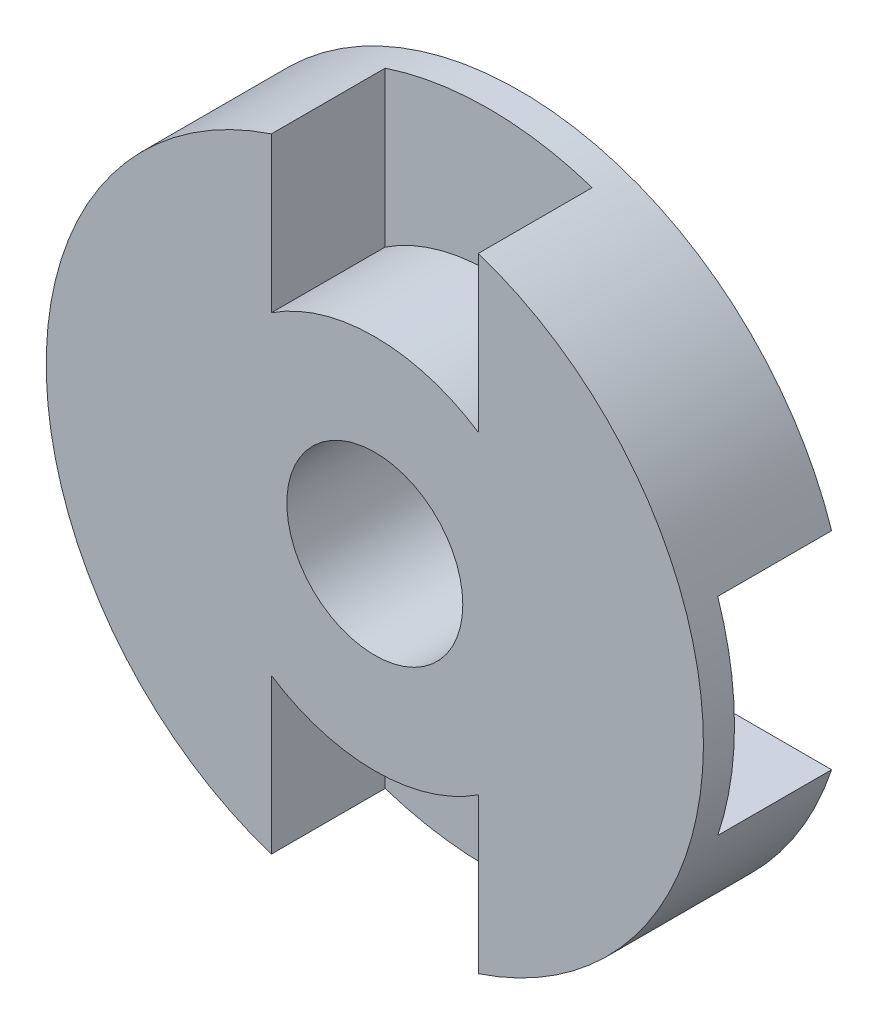
SolidWorks part; units mm, degrees
ref_plane "Front" through (0, 0, 0) normal (0, 0, 1) x (1, 0, 0)
ref_plane "Top" through (0, 0, 0) normal (0, 1, 0) x (1, 0, 0)
ref_plane "Right" through (0, 0, 0) normal (1, 0, 0) x (0, 0, -1)
sketch "Sketch1" plane through (0, 0, 0) normal (0, 0, 1) x (1, 0, 0)
  circle A0 centre (0, 0) radius 6.35
  point P3 (0, 6.35)
extrude "Boss-Extrude1" add sketch "Sketch1" against normal mid plane 2.8
sketch "Sketch2" plane through (0, 0, 1.4) normal (0, 0, 1) x (1, 0, 0)
  line L0 (-2, 6.35) -> (2, -6.35) construction
  line L1 (-2, 6.35) -> (2, 6.35)
  line L2 (-2, 6.35) -> (-2, -6.35)
  line L3 (-2, -6.35) -> (2, -6.35)
  line L4 (2, 6.35) -> (2, -6.35)
  circle A0 centre (0, 0) radius 6.35 construction
extrude "Cut-Extrude1" cut sketch "Sketch2" against normal blind 2.2
sketch "Sketch3" plane through (0, 0, -1.4) normal (0, 0, -1) x (-1, 0, 0)
  line L1 (-6.35, 2) -> (6.35, 2)
  line L2 (-6.35, 2) -> (-6.35, -2)
  line L3 (-6.35, -2) -> (6.35, -2)
  line L4 (6.35, 2) -> (6.35, -2)
  line L14 (2, 6.35) -> (-2, 6.35) construction
  line L15 (6.35, 2) -> (-6.35, -2) construction
  circle A0 centre (0, 0) radius 6.35 construction
extrude "Cut-Extrude2" cut sketch "Sketch3" against normal blind 2.2
sketch "Sketch4" [suppressed] plane through (0, 0, 8.5344) normal (0, 0, 1) x (1, 0, 0)
  line L0 (-5.0483, 0) -> (-8.6297, 0) construction
  line L1 (16.6687, 16.6688) -> (8.6297, 16.6687)
  line L2 (16.6687, 16.6688) -> (16.6687, -16.6688)
  line L3 (16.6687, -16.6688) -> (8.6297, -16.6687)
  line L4 (8.6297, 16.6687) -> (8.6297, -16.6687)
  line L5 (-16.6688, 16.6688) -> (-8.6297, 16.6687)
  line L6 (-16.6688, 16.6688) -> (-16.6688, -16.6688)
  line L7 (-16.6688, -16.6688) -> (-8.6297, -16.6687)
  line L8 (-8.6297, 16.6687) -> (-8.6297, -16.6687)
  line L9 (-5.0483, 15.8859) -> (-5.0483, -15.8859) construction
  line L10 (5.0482, 0) -> (8.6297, 0) construction
  line L11 (5.0483, -15.8859) -> (5.0483, 15.8859) construction
  line L12 (-5.0483, 16.6687) -> (5.0483, 16.6687) construction
  line L13 (-5.0483, -16.6688) -> (5.0483, -16.6688) construction
  line L14 (5.0483, 16.6687) -> (5.0483, -16.6688) construction
  circle A1 centre (0, 0) radius 16.6687 construction
extrude "Cut-Extrude3" [suppressed] cut sketch "Sketch4" against normal blind 0.508
sketch "Sketch5" [suppressed] plane through (0, 0, -8.5344) normal (0, 0, -1) x (-1, 0, 0)
  line L0 (-16.6687, 16.6688) -> (-8.6297, 16.6687) construction
  line L1 (-16.6687, 16.6688) -> (16.6687, 16.6688)
  line L2 (-16.6687, 16.6688) -> (-16.6688, 8.6297)
  line L3 (-16.6688, 8.6297) -> (16.6688, 8.6297)
  line L4 (16.6687, 16.6688) -> (16.6688, 8.6297)
  line L5 (16.6687, -16.6687) -> (-16.6687, -16.6687)
  line L6 (16.6687, -16.6687) -> (16.6687, -8.6297)
  line L7 (16.6687, -8.6297) -> (-16.6687, -8.6297)
  line L8 (-16.6687, -16.6687) -> (-16.6687, -8.6297)
  line L9 (0, 5.0483) -> (0, 8.6297) construction
  line L10 (-15.8859, 5.0483) -> (15.8859, 5.0483) construction
  line L11 (-16.6687, 5.0483) -> (-16.6687, -5.0482) construction
  line L12 (0, -8.6297) -> (0, -5.0482) construction
  line L13 (-15.8859, -5.0482) -> (15.8859, -5.0482) construction
  circle A0 centre (0, 0) radius 16.6687 construction
extrude "Cut-Extrude4" [suppressed] cut sketch "Sketch5" against normal blind 0.508
chamfer "Chamfer1" [suppressed] distance 3.8186 angle 30
sketch "Sketch6" [suppressed] plane through (0, 0, 8.5344) normal (0, 0, 1) x (1, 0, 0)
  line L0 (-5.3007, 6.0424) -> (5.3007, -6.0424) construction
  line L1 (-5.3007, 6.0424) -> (5.3007, 6.0424)
  line L2 (-5.3007, 6.0424) -> (-5.3007, -6.0424)
  line L3 (-5.3007, -6.0424) -> (5.3007, -6.0424)
  line L4 (5.3007, 6.0424) -> (5.3007, -6.0424)
  dimension "D1" = 4.2
  dimension "D2" = 4.6037
extrude "Cut-Extrude5" [suppressed] cut sketch "Sketch6" against normal up to surface (8.001 mm away)
sketch "Sketch7" [suppressed] plane through (0, 0, -8.5344) normal (0, 0, -1) x (-1, 0, 0)
  line L0 (-6.0424, 5.3007) -> (6.0424, -5.3007) construction
  line L1 (-6.0424, 5.3007) -> (6.0424, 5.3007)
  line L2 (-6.0424, 5.3007) -> (-6.0424, -5.3007)
  line L3 (-6.0424, -5.3007) -> (6.0424, -5.3007)
  line L4 (6.0424, 5.3007) -> (6.0424, -5.3007)
  line L5 (5.3007, 6.0424) -> (5.3007, -6.0424) construction
  line L6 (5.3007, 6.0424) -> (-5.3007, 6.0424) construction
extrude "Cut-Extrude6" [suppressed] cut sketch "Sketch7" against normal up to surface (8.001 mm away)
sketch "Sketch8" plane through (0, 0, 0) normal (1, 0, 0) x (0, 0, -1)
  line L0 (-1.4, 6.0268) -> (-1.4, -6.0268) construction
  line L2 (1.4, 2) -> (1.4, 6.35) construction
  point P0 (1.4, 6.35)
  point P1 (-1.4, 6.35)
sketch "Sketch9" plane through (0, 0, -0.8) normal (0, 0, 1) x (1, 0, 0)
  circle A0 centre (0, 0) radius 3.633
  circle A1 centre (0, 0) radius 1.7
  dimension "D1" = 7.266
  dimension "D2" = 3.4
extrude "Boss-Extrude2" add sketch "Sketch9" along normal up to surface and the other way up to surface up to face at (-4.175, 0, 1.4) other way up to face at (0, 4.175, -1.4)
sketch "Sketch10" plane through (0, 0, -1.4) normal (0, 0, -1) x (-1, 0, 0)
  circle A0 centre (0, 0) radius 1.7
equation "\"D1@Cut-Extrude2\" = \"Tooth depth@Cut-Extrude1\""
equation "\"D1@Cut-Extrude4\" = \"Tooth depth 2@Cut-Extrude3\""
equation "\"D1@Chamfer1\" = \"D1@Sketch4\" * .475"
equation "\"D1@Sketch6\" = \"Tooth gap@Sketch2\" * 1.05"
equation "\"D2@Sketch6\" = \"OD@Sketch1\" * .3625"
